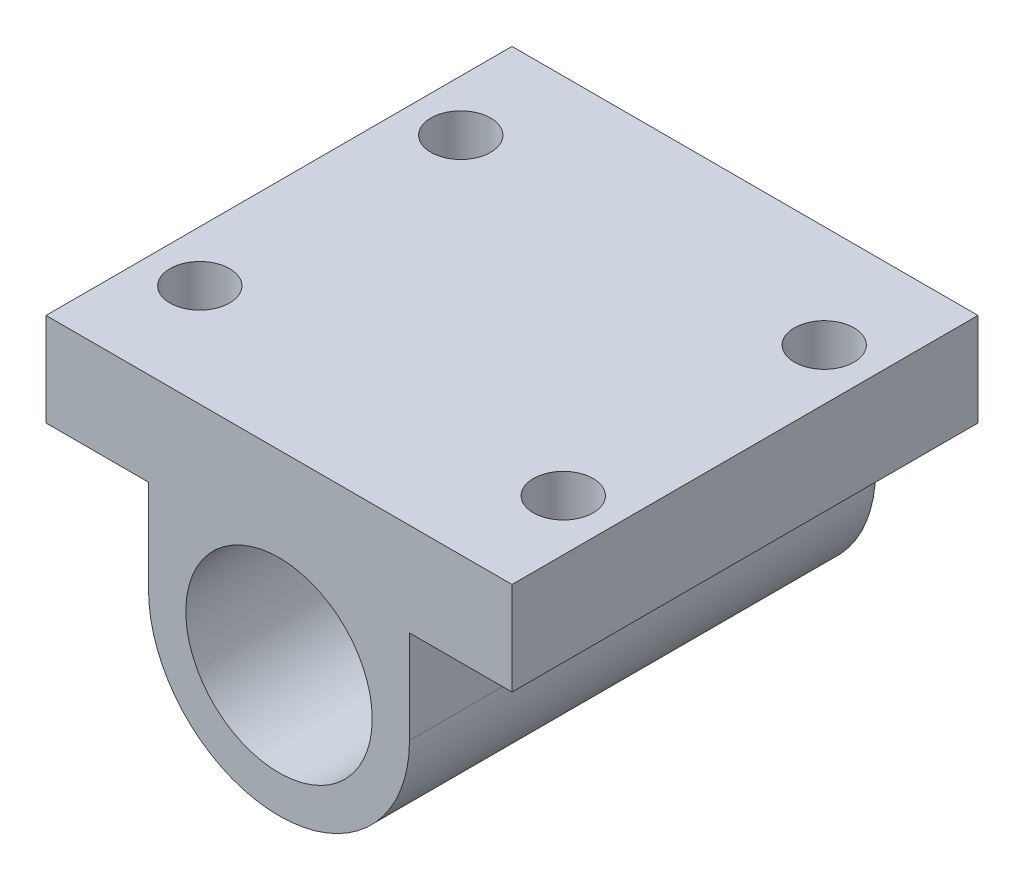
SolidWorks part; units mm, degrees
ref_plane "Płaszczyzna przednia" through (0, 0, 0) normal (0, 0, 1) x (1, 0, 0)
ref_plane "Płaszczyzna górna" through (0, 0, 0) normal (0, 1, 0) x (1, 0, 0)
ref_plane "Płaszczyzna prawa" through (0, 0, 0) normal (1, 0, 0) x (0, 0, -1)
sketch "Szkic1" plane through (0, 0, 0) normal (0, 0, 1) x (1, 0, 0)
  line L0 (-7, -5) -> (-7, 0)
  line L1 (-12.5, 5) -> (12.5, 5)
  line L2 (-12.5, 5) -> (-12.5, 0)
  line L3 (-12.5, 0) -> (-7, 0)
  line L4 (12.5, 5) -> (12.5, 0)
  line L5 (0, 0) -> (0, 5) construction
  line L6 (-12.5, 2.5) -> (12.5, 2.5) construction
  line L7 (7, -5) -> (7, 0)
  line L8 (7, 0) -> (12.5, 0)
  circle A0 centre (0, -5) radius 5
  arc A1 (-7, -5) -> (7, -5) centre (0, -5) ccw
  point P140 (0, 2.5)
  dimension "D1" = 10
  dimension "D2" = 2
  dimension "D3" = 25
  dimension "D4" = 5
extrude "Dodanie-wyciągnięcie1" add sketch "Szkic1" along normal blind 25
sketch "Szkic2" plane through (0, 0, 0) normal (0, -1, 0) x (1, 0, 0)
  line L0 (-9.75, 25) -> (-9.75, 0) construction
  line L1 (-12.5, 25) -> (-7, 25) construction
  line L2 (-12.5, 0) -> (-7, 0) construction
  line L3 (-12.5, 12.5) -> (-7, 12.5) construction
  line L4 (-12.5, 25) -> (-12.5, 0) construction
  line L5 (-7, 25) -> (-7, 0) construction
  line L6 (0, 25) -> (0, 0) construction
  line L7 (7, 25) -> (-7, 25) construction
  line L8 (-7, 0) -> (7, 0) construction
  point P6 (-9.75, 19.5)
  point P13 (-9.75, 5.5)
  point P20 (9.75, 5.5)
  point P21 (9.75, 19.5)
  dimension "D1" = 7
hole_wizard "Otwór Ø3.2 (3.2)1" positions "Szkic2" profile "Szkic3" hole size "Ø3.2" standard "DIN"
sketch "Szkic3" plane through (9.75, 0, 19.5) normal (1, 0, 0) x (0, 0, -1)
  line L0 (0, 0) -> (0, 5.9614)
  line L1 (0, 5.9614) -> (1.6, 5)
  line L2 (1.6, 5) -> (1.6, 0)
  line L5 (1.6, 0) -> (0, 0)
  line L10 (0, 5.9614) -> (-1.6, 5) construction
  line L11 (0, -6.35) -> (0, 107.95) construction
  dimension "Średnica otworu" = 3.2
  dimension "Głębokość otworu" = 5
  dimension "Kąt wiertła" = 118
